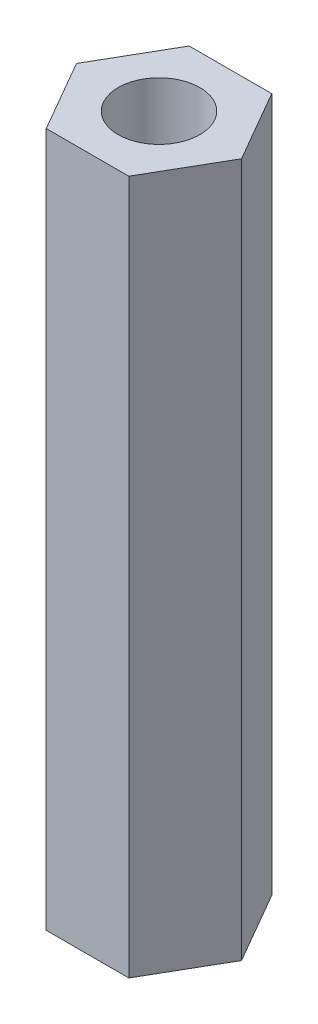
SolidWorks part; units mm, degrees
ref_plane "Front Plane" through (0, 0, 0) normal (0, 0, 1) x (1, 0, 0)
ref_plane "Top Plane" through (0, 0, 0) normal (0, 1, 0) x (1, 0, 0)
ref_plane "Right Plane" through (0, 0, 0) normal (1, 0, 0) x (0, 0, -1)
sketch "Sketch1" plane through (0, 0, 0) normal (0, 1, 0) x (1, 0, 0)
  line L1 (2.0207, 3.5) -> (-2.0207, 3.5)
  line L2 (-2.0207, 3.5) -> (-4.0415, 0)
  line L3 (-4.0415, 0) -> (-2.0207, -3.5)
  line L4 (-2.0207, -3.5) -> (2.0207, -3.5)
  line L5 (2.0207, -3.5) -> (4.0415, 0)
  line L6 (4.0415, 0) -> (2.0207, 3.5)
  circle A0 centre (0, 0) radius 3.5 construction
  circle A1 centre (0, 0) radius 2
  dimension "D1" = 7
  dimension "D2" = 4
extrude "Boss-Extrude1" add sketch "Sketch1" along normal blind 34
